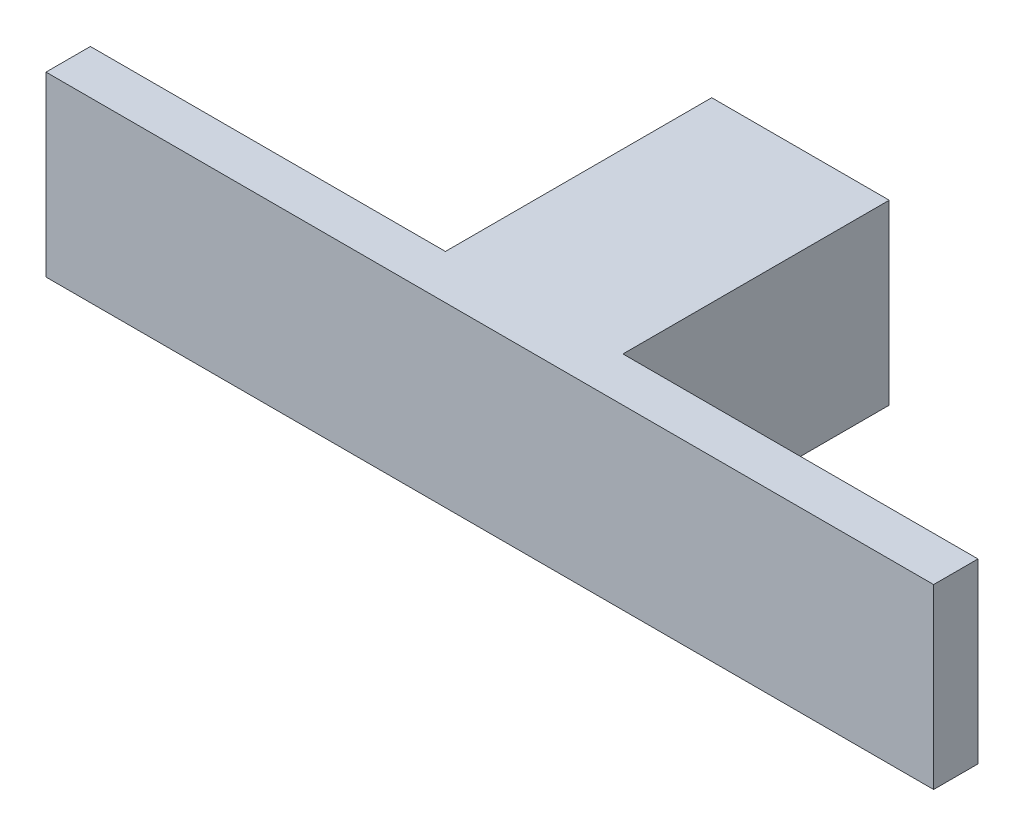
SolidWorks part; units mm, degrees
ref_plane "Přední rovina" through (0, 0, 0) normal (0, 0, 1) x (1, 0, 0)
ref_plane "Horní rovina" through (0, 0, 0) normal (0, 1, 0) x (1, 0, 0)
ref_plane "Pravá rovina" through (0, 0, 0) normal (1, 0, 0) x (0, 0, -1)
sketch "Sketch2" plane through (0, 0, 0) normal (0, 1, 0) x (1, 0, 0)
  line L0 (0, -35) -> (0, 0) construction
  line L1 (50, -35) -> (-50, -35)
  line L2 (50, -35) -> (50, -30)
  line L3 (50, -30) -> (10, -30)
  line L7 (-10, 0) -> (10, 0)
  line L8 (10, -30) -> (10, 0)
  line L9 (-10, -30) -> (-10, 0)
  line L10 (-50, -30) -> (-10, -30)
  line L11 (-50, -35) -> (-50, -30)
  dimension "D1" = 50
  dimension "D2" = 5
  dimension "D3" = 30
  dimension "D4" = 10
extrude "Boss-Extrude1" add sketch "Sketch2" along normal blind 20
